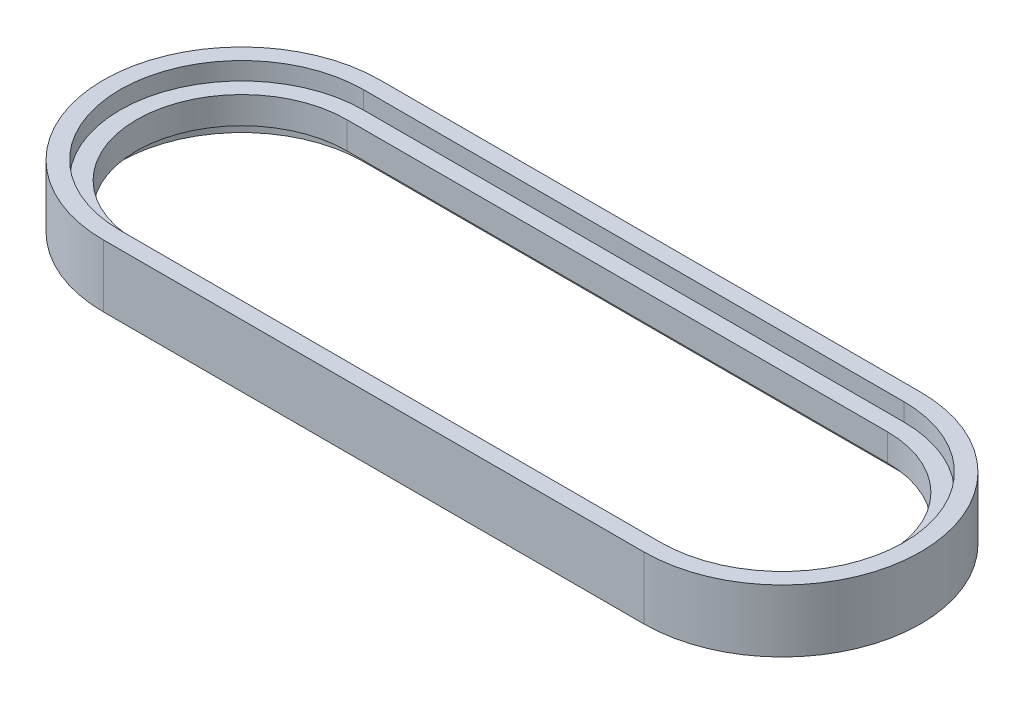
SolidWorks part; units mm, degrees
ref_plane "Front Plane" through (0, 0, 0) normal (0, 0, 1) x (1, 0, 0)
ref_plane "Top Plane" through (0, 0, 0) normal (0, 1, 0) x (1, 0, 0)
ref_plane "Right Plane" through (0, 0, 0) normal (1, 0, 0) x (0, 0, -1)
sketch "Sketch1" plane through (0, 0, 0) normal (0, 1, 0) x (1, 0, 0)
  line L0 (0, 0) -> (260, 0) construction
  line L1 (0, 58.57) -> (260, 58.57)
  line L2 (0, -58.57) -> (260, -58.57)
  line L3 (0, 66.57) -> (260, 66.57)
  line L4 (0, -66.57) -> (260, -66.57)
  arc A0 (0, 58.57) -> (0, -58.57) centre (0, 0) ccw
  arc A1 (260, -58.57) -> (260, 58.57) centre (260, 0) ccw
  arc A2 (260, -66.57) -> (260, 66.57) centre (260, 0) ccw
  arc A3 (0, 66.57) -> (0, -66.57) centre (0, 0) ccw
  point P3 (130, 0)
  dimension "D2" = 184.0031
  dimension "D1" = 260
  dimension "D3" = 8
extrude "Boss-Extrude1" add sketch "Sketch1" along normal blind 30
ref_plane "Plane1" through (0, 15, 0) normal (0, -1, 0) x (-1, 0, 0)
sketch "Sketch2" plane through (0, 15, 0) normal (0, -1, 0) x (-1, 0, 0)
  line L0 (0, 0) -> (-260, 0) construction
  line L1 (0, -58.57) -> (-260, -58.57)
  line L2 (0, 58.57) -> (-260, 58.57)
  line L3 (0, -50.57) -> (-260, -50.57)
  line L4 (0, 50.57) -> (-260, 50.57)
  arc A0 (0, -58.57) -> (0, 58.57) centre (0, 0) ccw
  arc A1 (-260, 58.57) -> (-260, -58.57) centre (-260, 0) ccw
  arc A2 (-260, 58.57) -> (-260, -58.57) centre (-260, 0) ccw construction
  arc A3 (-260, 50.57) -> (-260, -50.57) centre (-260, 0) ccw
  arc A4 (0, -50.57) -> (0, 50.57) centre (0, 0) ccw
  point P3 (-130, 0)
  dimension "D1" = 8
extrude "Boss-Extrude2" add sketch "Sketch2" along normal blind 6.5 and the other way blind 6.5
